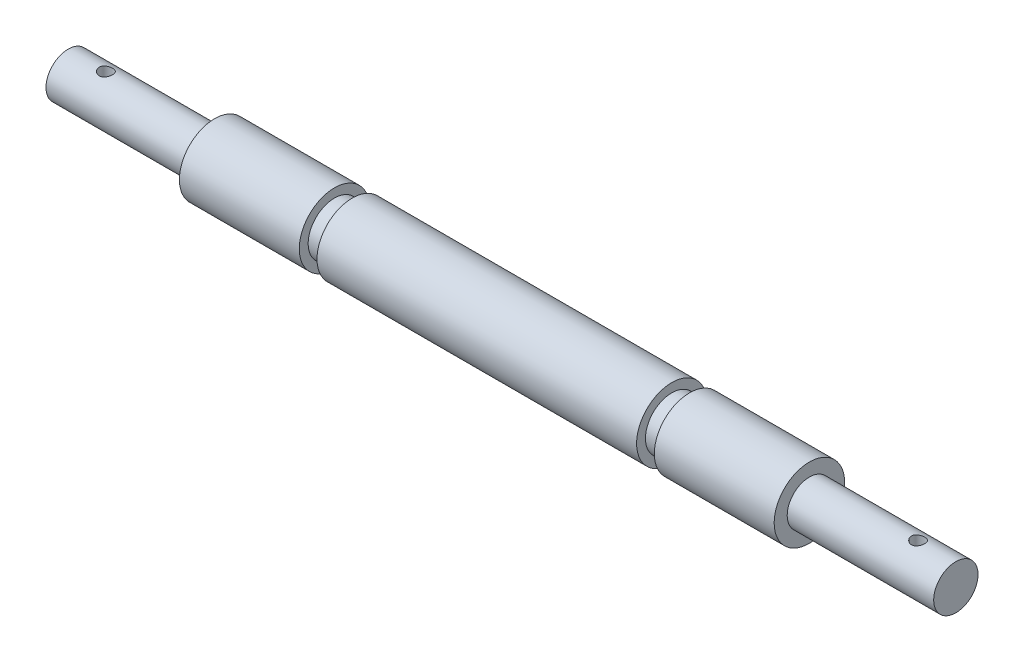
SolidWorks part; units mm, degrees
material "Barra Redonda Tref. SAE 1020 - 5/8\""
ref_plane "Plano frontal" through (0, 0, 0) normal (0, 0, 1) x (1, 0, 0)
ref_plane "Plano superior" through (0, 0, 0) normal (0, 1, 0) x (1, 0, 0)
ref_plane "Plano direito" through (0, 0, 0) normal (1, 0, 0) x (0, 0, -1)
sketch "Esboço2" plane through (0, 0, 0) normal (0, 0, 1) x (1, 0, 0)
  line L0 (0, 0) -> (0, 47.7147) construction
  line L1 (0, 0) -> (-156.5589, 0) construction
  line L2 (67, 7.9375) -> (40, 7.9375)
  line L3 (-67, 7.9375) -> (-67, 5)
  line L4 (-67, 5) -> (-100, 5)
  line L5 (-100, 5) -> (-100, 0)
  line L6 (67, 7.9375) -> (67, 5)
  line L7 (100, 5) -> (100, 0)
  line L8 (67, 5) -> (100, 5)
  line L9 (-100, 0) -> (100, 0)
  line L10 (-40, 7.9375) -> (-67, 7.9375)
  line L11 (40, 7.9375) -> (40, 5.9375)
  line L12 (-36, 7.9375) -> (-36, 5.9375)
  line L13 (-36, 5.9375) -> (-40, 5.9375)
  line L14 (-40, 7.9375) -> (-40, 5.9375)
  line L15 (36, 5.9375) -> (40, 5.9375)
  line L16 (36, 7.9375) -> (36, 5.9375)
  line L17 (36, 7.9375) -> (-36, 7.9375)
  point P11 (0, 7.9375)
  dimension "D1" = 134
  dimension "D2" = 33
  dimension "D3" = 10
  dimension "D4" = 15.875
  dimension "D5" = 2
  dimension "D6" = 4
  dimension "D7" = 40
revolve "Revolução1" add sketch "Esboço2" angle 360 about L9
cosmetic thread "Representação de rosca1" parameters "D1"=18, "D2"=8.344
cosmetic thread "Representação de rosca2" parameters "D1"=18, "D2"=8.344
sketch "Esboço3" plane through (0, 0, 0) normal (0, 1, 0) x (1, 0, 0)
  line L0 (-67, 0) -> (-91.5, 0) construction
  line L3 (-67, 5) -> (-67, -5) construction
  circle A0 centre (-91.5, 0) radius 1.5
  dimension "D1" = 3
  dimension "D2" = 24.5
extrude "Corte-extrusão1" cut sketch "Esboço3" against normal through all and the other way through all
mirror "Espelhar1" about plane through (0, 0, 0) normal (1, 0, 0) of "Corte-extrusão1"
